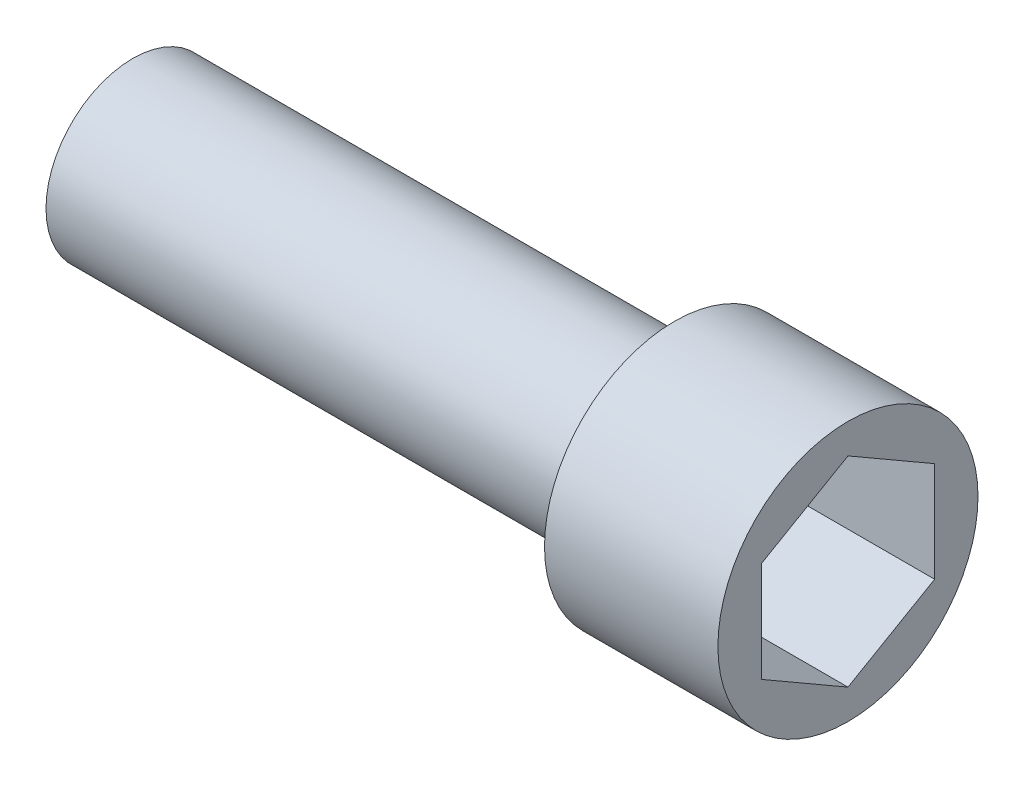
SolidWorks part; units mm, degrees
ref_plane "Front Plane" through (0, 0, 0) normal (1, 0, 0) x (0, 1, 0)
ref_plane "Top Plane" through (0, 0, 0) normal (0, 0, 1) x (0, 1, 0)
ref_plane "Right Plane" through (0, 0, 0) normal (0, 1, 0) x (-1, 0, 0)
sketch "Sketch1" plane through (0, 0, 0) normal (1, 0, 0) x (0, 1, 0)
  circle A0 centre (0, 0) radius 6
  dimension "D1" = 12
extrude "Boss-Extrude1" add sketch "Sketch1" along normal blind 8
sketch "Sketch2" plane through (8, 0, 0) normal (1, 0, 0) x (0, 1, 0)
  line L1 (4.6188, 0) -> (2.3094, 4)
  line L2 (2.3094, 4) -> (-2.3094, 4)
  line L3 (-2.3094, 4) -> (-4.6188, 0)
  line L4 (-4.6188, 0) -> (-2.3094, -4)
  line L5 (-2.3094, -4) -> (2.3094, -4)
  line L6 (2.3094, -4) -> (4.6188, 0)
  circle A0 centre (0, 0) radius 4 construction
  dimension "D1" = 8
extrude "Cut-Extrude1" cut sketch "Sketch2" against normal blind 6
sketch "Sketch3" plane through (0, 0, 0) normal (-1, 0, 0) x (0, -1, 0)
  circle A0 centre (0, 0) radius 4
  dimension "D1" = 8
extrude "Boss-Extrude2" add sketch "Sketch3" along normal blind 25
